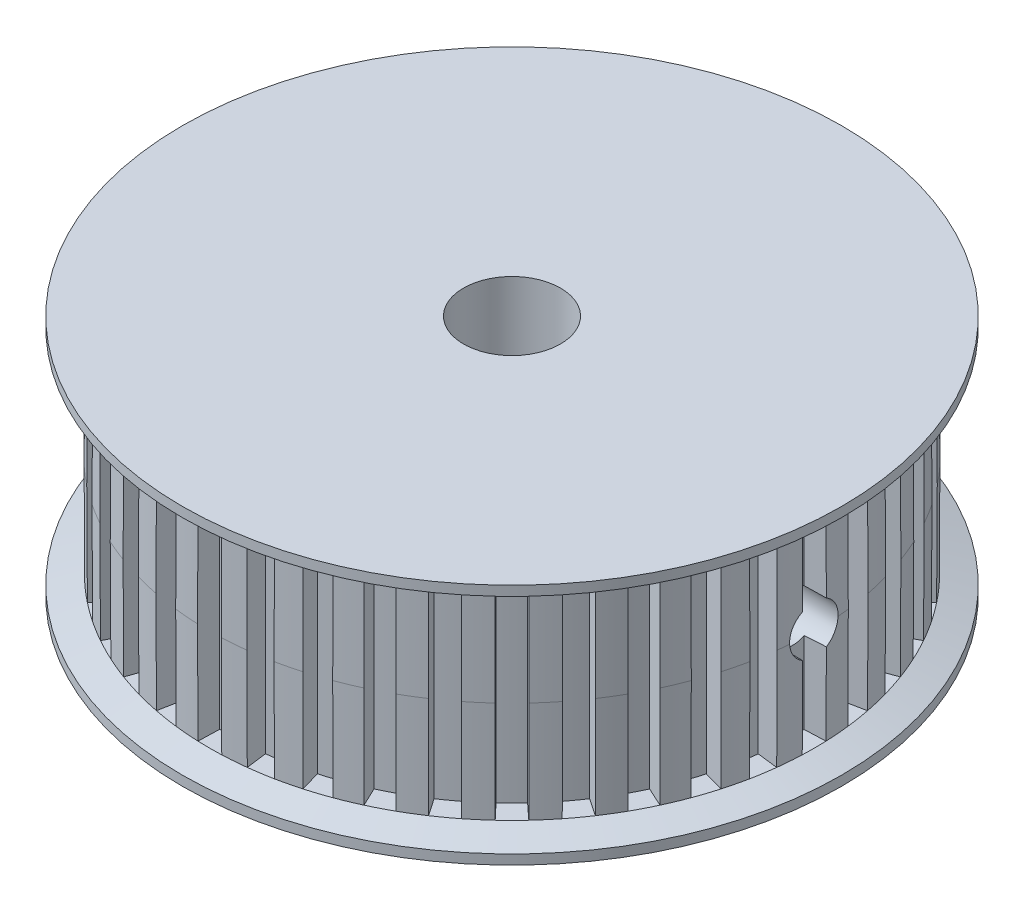
SolidWorks part; units mm, degrees
ref_plane "前视基准面" through (0, 0, 0) normal (0, 0, 1) x (1, 0, 0)
ref_plane "上视基准面" through (0, 0, 0) normal (0, 1, 0) x (1, 0, 0)
ref_plane "右视基准面" through (0, 0, 0) normal (1, 0, 0) x (0, 0, -1)
sketch "草图1" plane through (0, 0, 0) normal (0, 1, 0) x (1, 0, 0)
  circle A0 centre (0, 0) radius 34
  dimension "D1" = 68
extrude "凸台-拉伸1" add sketch "草图1" along normal blind 2
sketch "草图2" plane through (0, 2, 0) normal (0, 1, 0) x (1, 0, 0)
  circle A0 centre (0, 0) radius 31.25
  dimension "D1" = 62.5
extrude "凸台-拉伸2" add sketch "草图2" along normal blind 21
sketch "草图4" plane through (0, 23, 0) normal (0, 1, 0) x (1, 0, 0)
  line L0 (0, 0) -> (0, 47.8751) construction
  line L1 (0, 0) -> (1.4466, 36.818) construction
  line L2 (0, 0) -> (-1.4503, 36.9128) construction
  line L3 (1.1655, 28.9766) -> (1.2269, 31.2259)
  line L4 (-1.1385, 28.9776) -> (-1.2269, 31.2259)
  line L5 (3.4086, 28.799) -> (3.673, 31.0334)
  line L6 (5.6841, 28.4375) -> (6.0966, 30.6495)
  line L7 (7.8718, 27.9112) -> (8.4825, 30.0767)
  line L8 (10.0627, 27.1982) -> (10.8162, 29.3185)
  line L9 (12.1411, 26.3362) -> (13.0831, 28.3795)
  line L10 (14.1935, 25.2892) -> (15.2694, 27.2655)
  line L11 (16.1115, 24.1126) -> (17.3616, 25.9834)
  line L12 (17.9749, 22.7575) -> (19.3467, 24.5412)
  line L13 (19.6852, 21.2954) -> (21.2125, 22.9476)
  line L14 (21.3136, 19.6654) -> (22.9476, 21.2125)
  line L15 (22.7742, 17.9537) -> (24.5412, 19.3467)
  line L16 (24.1276, 16.0891) -> (25.9834, 17.3616)
  line L17 (25.3024, 14.17) -> (27.2655, 15.2694)
  line L18 (26.3474, 12.1167) -> (28.3795, 13.0831)
  line L19 (27.2075, 10.0374) -> (29.3185, 10.8162)
  line L20 (27.9185, 7.8458) -> (30.0767, 8.4825)
  line L21 (28.4428, 5.6576) -> (30.6495, 6.0966)
  line L22 (28.8021, 3.3818) -> (31.0334, 3.673)
  line L23 (28.9776, 1.1385) -> (31.2259, 1.2269)
  line L24 (28.9766, -1.1655) -> (31.2259, -1.2269)
  line L25 (28.799, -3.4086) -> (31.0334, -3.673)
  line L26 (28.4375, -5.6841) -> (30.6495, -6.0966)
  line L27 (27.9112, -7.8718) -> (30.0767, -8.4825)
  line L28 (27.1982, -10.0627) -> (29.3185, -10.8162)
  line L29 (26.3362, -12.1411) -> (28.3795, -13.0831)
  line L30 (25.2892, -14.1935) -> (27.2655, -15.2694)
  line L31 (24.1126, -16.1115) -> (25.9834, -17.3616)
  line L32 (22.7575, -17.9749) -> (24.5412, -19.3467)
  line L33 (21.2954, -19.6852) -> (22.9476, -21.2125)
  line L34 (19.6654, -21.3136) -> (21.2125, -22.9476)
  line L35 (17.9537, -22.7742) -> (19.3467, -24.5412)
  line L36 (16.0891, -24.1276) -> (17.3616, -25.9834)
  line L37 (14.17, -25.3024) -> (15.2694, -27.2655)
  line L38 (12.1167, -26.3474) -> (13.0831, -28.3795)
  line L39 (10.0374, -27.2075) -> (10.8162, -29.3185)
  line L40 (7.8458, -27.9185) -> (8.4825, -30.0767)
  line L41 (5.6576, -28.4428) -> (6.0966, -30.6495)
  line L42 (3.3818, -28.8021) -> (3.673, -31.0334)
  line L43 (1.1385, -28.9776) -> (1.2269, -31.2259)
  line L44 (-1.1655, -28.9766) -> (-1.2269, -31.2259)
  line L45 (-3.4086, -28.799) -> (-3.673, -31.0334)
  line L46 (-5.6841, -28.4375) -> (-6.0966, -30.6495)
  line L47 (-7.8718, -27.9112) -> (-8.4825, -30.0767)
  line L48 (-10.0627, -27.1982) -> (-10.8162, -29.3185)
  line L49 (-12.1411, -26.3362) -> (-13.0831, -28.3795)
  line L50 (-14.1935, -25.2892) -> (-15.2694, -27.2655)
  line L51 (-16.1115, -24.1126) -> (-17.3616, -25.9834)
  line L52 (-17.9749, -22.7575) -> (-19.3467, -24.5412)
  line L53 (-19.6852, -21.2954) -> (-21.2125, -22.9476)
  line L54 (-21.3136, -19.6654) -> (-22.9476, -21.2125)
  line L55 (-22.7742, -17.9537) -> (-24.5412, -19.3467)
  line L56 (-24.1276, -16.0891) -> (-25.9834, -17.3616)
  line L57 (-25.3024, -14.17) -> (-27.2655, -15.2694)
  line L58 (-26.3474, -12.1167) -> (-28.3795, -13.0831)
  line L59 (-27.2075, -10.0374) -> (-29.3185, -10.8162)
  line L60 (-27.9185, -7.8458) -> (-30.0767, -8.4825)
  line L61 (-28.4428, -5.6576) -> (-30.6495, -6.0966)
  line L62 (-28.8021, -3.3818) -> (-31.0334, -3.673)
  line L63 (-28.9776, -1.1385) -> (-31.2259, -1.2269)
  line L64 (-28.9766, 1.1655) -> (-31.2259, 1.2269)
  line L65 (-28.799, 3.4086) -> (-31.0334, 3.673)
  line L66 (-28.4375, 5.6841) -> (-30.6495, 6.0966)
  line L67 (-27.9112, 7.8718) -> (-30.0767, 8.4825)
  line L68 (-27.1982, 10.0627) -> (-29.3185, 10.8162)
  line L69 (-26.3362, 12.1411) -> (-28.3795, 13.0831)
  line L70 (-25.2892, 14.1935) -> (-27.2655, 15.2694)
  line L71 (-24.1126, 16.1115) -> (-25.9834, 17.3616)
  line L72 (-22.7575, 17.9749) -> (-24.5412, 19.3467)
  line L73 (-21.2954, 19.6852) -> (-22.9476, 21.2125)
  line L74 (-19.6654, 21.3136) -> (-21.2125, 22.9476)
  line L75 (-17.9537, 22.7742) -> (-19.3467, 24.5412)
  line L76 (-16.0891, 24.1276) -> (-17.3616, 25.9834)
  line L77 (-14.17, 25.3024) -> (-15.2694, 27.2655)
  line L78 (-12.1167, 26.3474) -> (-13.0831, 28.3795)
  line L79 (-10.0374, 27.2075) -> (-10.8162, 29.3185)
  line L80 (-7.8458, 27.9185) -> (-8.4825, 30.0767)
  line L81 (-5.6576, 28.4428) -> (-6.0966, 30.6495)
  line L82 (-3.3818, 28.8021) -> (-3.673, 31.0334)
  arc A0 (1.1655, 28.9766) -> (-1.1385, 28.9776) centre (0, 0) ccw
  circle A2 centre (0, 0) radius 31.25 construction
  circle A3 centre (0, 0) radius 31.25 construction
  arc A4 (1.2269, 31.2259) -> (-1.2269, 31.2259) centre (0, 0) ccw
  arc A5 (5.6841, 28.4375) -> (3.4086, 28.799) centre (0, 0) ccw
  arc A6 (6.0966, 30.6495) -> (3.673, 31.0334) centre (0, 0) ccw
  arc A7 (10.0627, 27.1982) -> (7.8718, 27.9112) centre (0, 0) ccw
  arc A8 (10.8162, 29.3185) -> (8.4825, 30.0767) centre (0, 0) ccw
  arc A9 (14.1935, 25.2892) -> (12.1411, 26.3362) centre (0, 0) ccw
  arc A10 (15.2694, 27.2655) -> (13.0831, 28.3795) centre (0, 0) ccw
  arc A11 (17.9749, 22.7575) -> (16.1115, 24.1126) centre (0, 0) ccw
  arc A12 (19.3467, 24.5412) -> (17.3616, 25.9834) centre (0, 0) ccw
  arc A13 (21.3136, 19.6654) -> (19.6852, 21.2954) centre (0, 0) ccw
  arc A14 (22.9476, 21.2125) -> (21.2125, 22.9476) centre (0, 0) ccw
  arc A15 (24.1276, 16.0891) -> (22.7742, 17.9537) centre (0, 0) ccw
  arc A16 (25.9834, 17.3616) -> (24.5412, 19.3467) centre (0, 0) ccw
  arc A17 (26.3474, 12.1167) -> (25.3024, 14.17) centre (0, 0) ccw
  arc A18 (28.3795, 13.0831) -> (27.2655, 15.2694) centre (0, 0) ccw
  arc A19 (27.9185, 7.8458) -> (27.2075, 10.0374) centre (0, 0) ccw
  arc A20 (30.0767, 8.4825) -> (29.3185, 10.8162) centre (0, 0) ccw
  arc A21 (28.8021, 3.3818) -> (28.4428, 5.6576) centre (0, 0) ccw
  arc A22 (31.0334, 3.673) -> (30.6495, 6.0966) centre (0, 0) ccw
  arc A23 (28.9766, -1.1655) -> (28.9776, 1.1385) centre (0, 0) ccw
  arc A24 (31.2259, -1.2269) -> (31.2259, 1.2269) centre (0, 0) ccw
  arc A25 (28.4375, -5.6841) -> (28.799, -3.4086) centre (0, 0) ccw
  arc A26 (30.6495, -6.0966) -> (31.0334, -3.673) centre (0, 0) ccw
  arc A27 (27.1982, -10.0627) -> (27.9112, -7.8718) centre (0, 0) ccw
  arc A28 (29.3185, -10.8162) -> (30.0767, -8.4825) centre (0, 0) ccw
  arc A29 (25.2892, -14.1935) -> (26.3362, -12.1411) centre (0, 0) ccw
  arc A30 (27.2655, -15.2694) -> (28.3795, -13.0831) centre (0, 0) ccw
  arc A31 (22.7575, -17.9749) -> (24.1126, -16.1115) centre (0, 0) ccw
  arc A32 (24.5412, -19.3467) -> (25.9834, -17.3616) centre (0, 0) ccw
  arc A33 (19.6654, -21.3136) -> (21.2954, -19.6852) centre (0, 0) ccw
  arc A34 (21.2125, -22.9476) -> (22.9476, -21.2125) centre (0, 0) ccw
  arc A35 (16.0891, -24.1276) -> (17.9537, -22.7742) centre (0, 0) ccw
  arc A36 (17.3616, -25.9834) -> (19.3467, -24.5412) centre (0, 0) ccw
  arc A37 (12.1167, -26.3474) -> (14.17, -25.3024) centre (0, 0) ccw
  arc A38 (13.0831, -28.3795) -> (15.2694, -27.2655) centre (0, 0) ccw
  arc A39 (7.8458, -27.9185) -> (10.0374, -27.2075) centre (0, 0) ccw
  arc A40 (8.4825, -30.0767) -> (10.8162, -29.3185) centre (0, 0) ccw
  arc A41 (3.3818, -28.8021) -> (5.6576, -28.4428) centre (0, 0) ccw
  arc A42 (3.673, -31.0334) -> (6.0966, -30.6495) centre (0, 0) ccw
  arc A43 (-1.1655, -28.9766) -> (1.1385, -28.9776) centre (0, 0) ccw
  arc A44 (-1.2269, -31.2259) -> (1.2269, -31.2259) centre (0, 0) ccw
  arc A45 (-5.6841, -28.4375) -> (-3.4086, -28.799) centre (0, 0) ccw
  arc A46 (-6.0966, -30.6495) -> (-3.673, -31.0334) centre (0, 0) ccw
  arc A47 (-10.0627, -27.1982) -> (-7.8718, -27.9112) centre (0, 0) ccw
  arc A48 (-10.8162, -29.3185) -> (-8.4825, -30.0767) centre (0, 0) ccw
  arc A49 (-14.1935, -25.2892) -> (-12.1411, -26.3362) centre (0, 0) ccw
  arc A50 (-15.2694, -27.2655) -> (-13.0831, -28.3795) centre (0, 0) ccw
  arc A51 (-17.9749, -22.7575) -> (-16.1115, -24.1126) centre (0, 0) ccw
  arc A52 (-19.3467, -24.5412) -> (-17.3616, -25.9834) centre (0, 0) ccw
  arc A53 (-21.3136, -19.6654) -> (-19.6852, -21.2954) centre (0, 0) ccw
  arc A54 (-22.9476, -21.2125) -> (-21.2125, -22.9476) centre (0, 0) ccw
  arc A55 (-24.1276, -16.0891) -> (-22.7742, -17.9537) centre (0, 0) ccw
  arc A56 (-25.9834, -17.3616) -> (-24.5412, -19.3467) centre (0, 0) ccw
  arc A57 (-26.3474, -12.1167) -> (-25.3024, -14.17) centre (0, 0) ccw
  arc A58 (-28.3795, -13.0831) -> (-27.2655, -15.2694) centre (0, 0) ccw
  arc A59 (-27.9185, -7.8458) -> (-27.2075, -10.0374) centre (0, 0) ccw
  arc A60 (-30.0767, -8.4825) -> (-29.3185, -10.8162) centre (0, 0) ccw
  arc A61 (-28.8021, -3.3818) -> (-28.4428, -5.6576) centre (0, 0) ccw
  arc A62 (-31.0334, -3.673) -> (-30.6495, -6.0966) centre (0, 0) ccw
  arc A63 (-28.9766, 1.1655) -> (-28.9776, -1.1385) centre (0, 0) ccw
  arc A64 (-31.2259, 1.2269) -> (-31.2259, -1.2269) centre (0, 0) ccw
  arc A65 (-28.4375, 5.6841) -> (-28.799, 3.4086) centre (0, 0) ccw
  arc A66 (-30.6495, 6.0966) -> (-31.0334, 3.673) centre (0, 0) ccw
  arc A67 (-27.1982, 10.0627) -> (-27.9112, 7.8718) centre (0, 0) ccw
  arc A68 (-29.3185, 10.8162) -> (-30.0767, 8.4825) centre (0, 0) ccw
  arc A69 (-25.2892, 14.1935) -> (-26.3362, 12.1411) centre (0, 0) ccw
  arc A70 (-27.2655, 15.2694) -> (-28.3795, 13.0831) centre (0, 0) ccw
  arc A71 (-22.7575, 17.9749) -> (-24.1126, 16.1115) centre (0, 0) ccw
  arc A72 (-24.5412, 19.3467) -> (-25.9834, 17.3616) centre (0, 0) ccw
  arc A73 (-19.6654, 21.3136) -> (-21.2954, 19.6852) centre (0, 0) ccw
  arc A74 (-21.2125, 22.9476) -> (-22.9476, 21.2125) centre (0, 0) ccw
  arc A75 (-16.0891, 24.1276) -> (-17.9537, 22.7742) centre (0, 0) ccw
  arc A76 (-17.3616, 25.9834) -> (-19.3467, 24.5412) centre (0, 0) ccw
  arc A77 (-12.1167, 26.3474) -> (-14.17, 25.3024) centre (0, 0) ccw
  arc A78 (-13.0831, 28.3795) -> (-15.2694, 27.2655) centre (0, 0) ccw
  arc A79 (-7.8458, 27.9185) -> (-10.0374, 27.2075) centre (0, 0) ccw
  arc A80 (-8.4825, 30.0767) -> (-10.8162, 29.3185) centre (0, 0) ccw
  arc A81 (-3.3818, 28.8021) -> (-5.6576, 28.4428) centre (0, 0) ccw
  arc A82 (-3.673, 31.0334) -> (-6.0966, 30.6495) centre (0, 0) ccw
  point P172 (0, 0)
  dimension "D1" = 2.25
  dimension "D2" = 2.25
  dimension "D3" = 2.25
  dimension "D4" = 40
extrude "切除-拉伸1" cut sketch "草图4" against normal up to surface (21 mm away) up to face at (0, 2, 31.25)
sketch "草图3" plane through (0, 23, 0) normal (0, 1, 0) x (1, 0, 0)
  circle A0 centre (0, 0) radius 34
  dimension "D1" = 68
extrude "凸台-拉伸3" add sketch "草图3" along normal blind 2
sketch "草图5" plane through (0, 0, 0) normal (1, 0, 0) x (0, 0, -1)
  line L0 (22.9476, 12.5) -> (-51.2022, 12.5) construction
  line L1 (22.9476, 2) -> (22.9476, 23) construction
  line L3 (34, 2) -> (-34, 2) construction
  line L4 (-31.1786, 2) -> (-31.2259, 12.5)
  line L5 (-31.2259, 2) -> (-31.2259, 23) construction
  line L8 (-31.1786, 23) -> (-31.2259, 12.5)
  line L10 (-31.1786, 2) -> (-34, 1)
  line L11 (-34, 2) -> (-34, 0) construction
  line L12 (-34, 1) -> (-34, 24)
  line L13 (-34, 25) -> (-34, 23) construction
  line L14 (-34, 24) -> (-31.1786, 23)
  point P15 (-34, 12.5)
sketch "草图6" plane through (0, 0, 0) normal (0, 1, 0) x (1, 0, 0)
  circle A0 centre (0, 0) radius 34 construction
  circle A1 centre (0, 0) radius 34
sweep "切除-扫描1" cut profiles "草图5" path "草图6"
sketch "草图7" plane through (0, 0, 0) normal (0, -1, 0) x (1, 0, 0)
  circle A0 centre (0, 0) radius 5
  dimension "D1" = 10
extrude "切除-拉伸2" cut sketch "草图7" against normal through all
ref_plane "基准面1" through (52, 0, 0) normal (1, 0, 0) x (0, 0, -1)
sketch "草图9" plane through (52, 0, 0) normal (1, 0, 0) x (0, 0, -1)
  line L0 (0, 0) -> (0, 37.5582) construction
  line L1 (-34, 0) -> (34, 0) construction
  circle A0 centre (0, 12.6195) radius 2.5
  dimension "D1" = 5
extrude "切除-拉伸3" cut sketch "草图9" against normal blind 50
